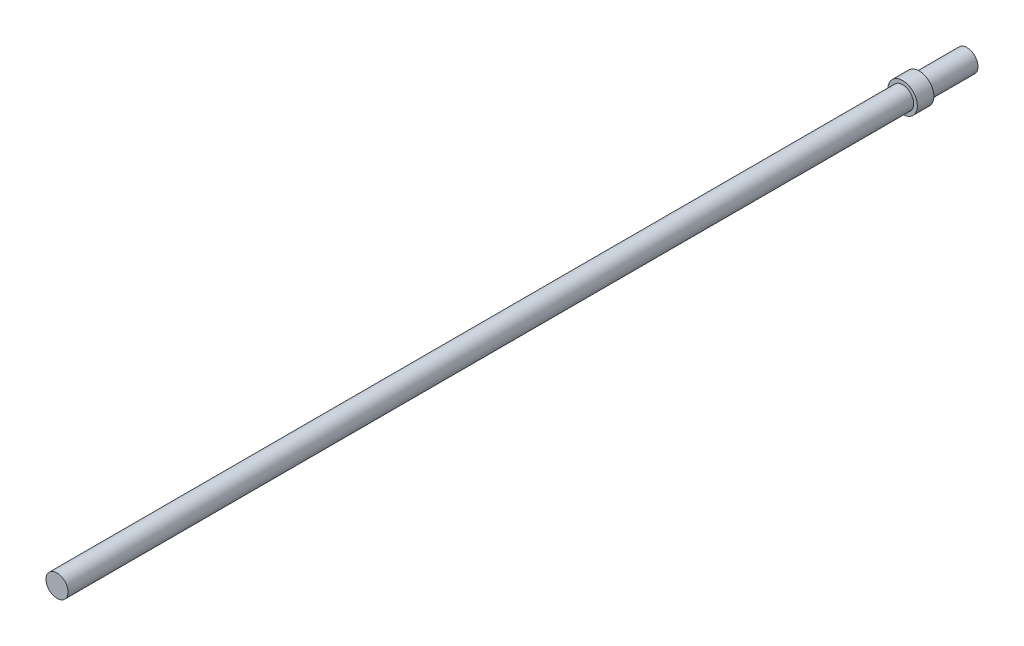
SolidWorks part; units mm, degrees
ref_plane "Front Plane" through (0, 0, 0) normal (0, 0, 1) x (1, 0, 0)
ref_plane "Top Plane" through (0, 0, 0) normal (0, 1, 0) x (1, 0, 0)
ref_plane "Right Plane" through (0, 0, 0) normal (1, 0, 0) x (0, 0, -1)
sketch "Sketch1" plane through (0, 0, 0) normal (0, 0, 1) x (1, 0, 0)
  circle A0 centre (0, 0) radius 3
extrude "Boss-Extrude1" add sketch "Sketch1" along normal blind 230
sketch "Sketch2" plane through (0, 0, 0) normal (0, 0, 1) x (1, 0, 0)
  circle A0 centre (0, 0) radius 4
extrude "Boss-Extrude2" add sketch "Sketch2" against normal blind 4.5
sketch "Sketch3" plane through (0, 0, 0) normal (0, 0, 1) x (1, 0, 0)
  circle A0 centre (0, 0) radius 3
extrude "Boss-Extrude3" add sketch "Sketch3" against normal blind 17.5
